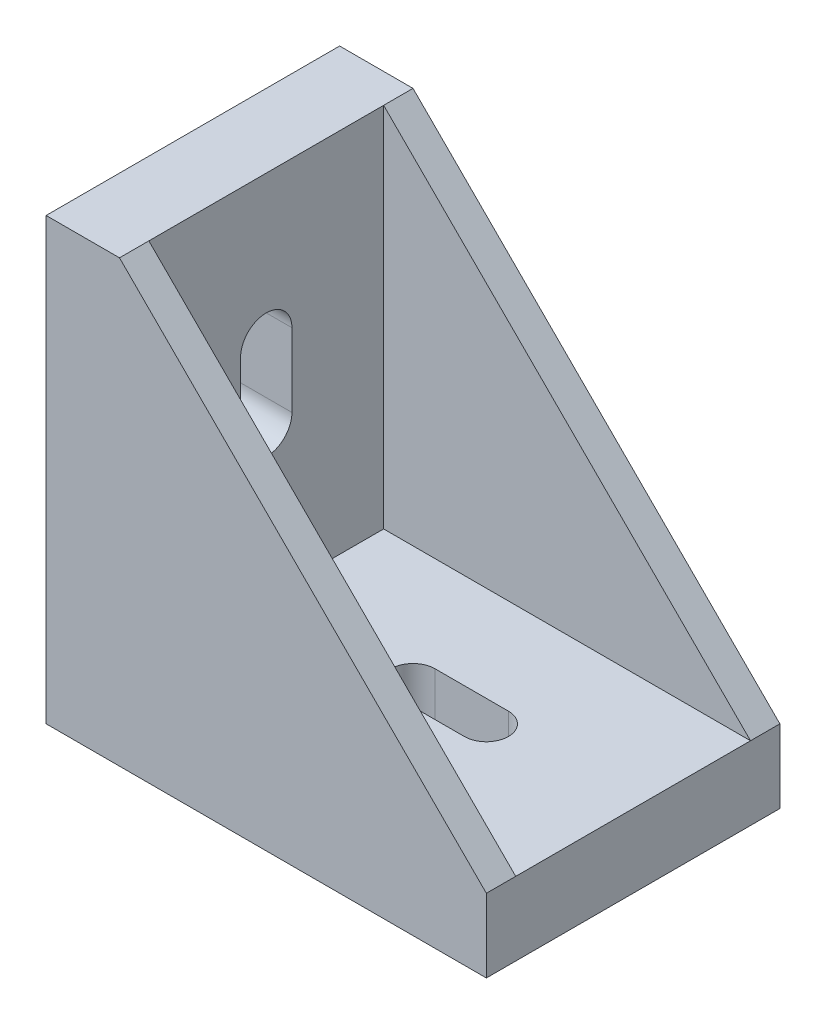
SolidWorks part; units mm, degrees
ref_plane "前基準面" through (0, 0, 0) normal (0, 0, 1) x (1, 0, 0)
ref_plane "上基準面" through (0, 0, 0) normal (0, 1, 0) x (1, 0, 0)
ref_plane "右基準面" through (0, 0, 0) normal (1, 0, 0) x (0, 0, -1)
sketch "草圖1" plane through (0, 0, 0) normal (0, 0, 1) x (1, 0, 0)
  line L0 (0, 0) -> (0, -30)
  line L1 (0, -30) -> (30, -30)
  line L2 (30, -30) -> (30, -25)
  line L3 (30, -25) -> (5, 0)
  line L4 (5, 0) -> (0, 0)
  dimension "D1" = 30
  dimension "D2" = 30
  dimension "D3" = 5
  dimension "D4" = 5
extrude "填料-伸長1" add sketch "草圖1" against normal blind 20
sketch "草圖3" plane through (30, 0, 0) normal (1, 0, 0) x (0, 0, -1)
  line L0 (20, 0) -> (0, 0) construction
  line L1 (2, 0) -> (18, 0)
  line L2 (2, 0) -> (2, -25)
  line L3 (2, -25) -> (18, -25)
  line L4 (18, 0) -> (18, -25)
  line L5 (20, -25) -> (0, -25) construction
  line L6 (20, -25) -> (20, 0) construction
  line L7 (0, -25) -> (0, 0) construction
  dimension "D1" = 2
  dimension "D2" = 2
extrude "除料-伸長1" cut sketch "草圖3" against normal blind 25
sketch "草圖4" plane through (5, 0, 0) normal (1, 0, 0) x (0, 0, -1)
  line L0 (10, -10) -> (10, -15) construction
  line L1 (11.75, -10) -> (11.75, -15)
  line L2 (8.25, -10) -> (8.25, -15)
  line L3 (18, 0) -> (2, 0) construction
  line L4 (20, -25) -> (20, 0) construction
  arc A0 (11.75, -10) -> (8.25, -10) centre (10, -10) ccw
  arc A1 (8.25, -15) -> (11.75, -15) centre (10, -15) ccw
  point P2 (10, -12.5)
  dimension "D1" = 3.5
  dimension "D2" = 5
  dimension "D3" = 10
  dimension "D4" = 10
extrude "除料-伸長2" cut sketch "草圖4" against normal up to next
sketch "草圖5" plane through (0, -25, 0) normal (0, 1, 0) x (1, 0, 0)
  line L0 (15, 10) -> (20, 10) construction
  line L1 (15, 11.5) -> (20, 11.5)
  line L2 (15, 8.5) -> (20, 8.5)
  line L4 (30, 20) -> (5, 20) construction
  line L6 (30, 2) -> (30, 18) construction
  arc A0 (15, 11.5) -> (15, 8.5) centre (15, 10) ccw
  arc A1 (20, 8.5) -> (20, 11.5) centre (20, 10) ccw
  point P2 (17.5, 10)
  dimension "D1" = 5
  dimension "D2" = 3
  dimension "D3" = 10
  dimension "D4" = 10
extrude "除料-伸長3" cut sketch "草圖5" against normal up to next
